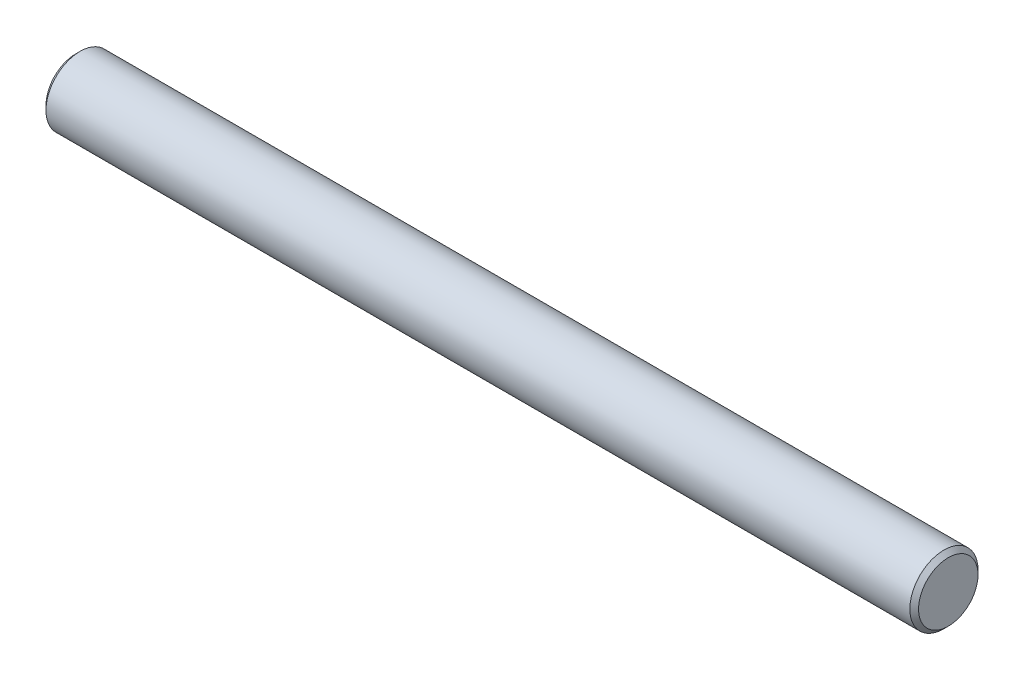
SolidWorks part; units mm, degrees
material "Plain Carbon Steel"
ref_plane "Спереди" through (0, 0, 0) normal (0, 0, 1) x (1, 0, 0)
ref_plane "Сверху" through (0, 0, 0) normal (0, 1, 0) x (1, 0, 0)
ref_plane "Справа" through (0, 0, 0) normal (1, 0, 0) x (0, 0, -1)
sketch "Sketch1" plane through (0, 0, 0) normal (0, 0, 1) x (1, 0, 0)
  line L0 (0, 0) -> (-128.9864, 0) construction
  line L1 (0, 0) -> (-320, 0)
  line L2 (-320, 0) -> (-320, 12.5)
  line L3 (-320, 12.5) -> (0, 12.5)
  line L4 (0, 12.5) -> (0, 0)
  dimension "D1" = 25
  dimension "D2" = 320
revolve "Revolve1" add sketch "Sketch1" angle 360 about L0
chamfer "Chamfer1" distance 1.6 angle 45 2 edges at (0, 0, -12.5) (-320, 0, -12.5)
hole_wizard "M10 Tapped Hole1" positions "Sketch3" profile "Sketch2" tap size "M10" standard "ISO"
sketch "Sketch3" plane through (-320, 0, 0) normal (-1, 0, 0) x (0, 0, 1)
  circle A0 centre (0, 0) radius 10.9 construction
  point P0 (0, 0)
sketch "Sketch2" plane through (-320, 0, 0) normal (0, 1, 0) x (0, 0, 1)
  line L0 (0, 0) -> (0, 27.0537)
  line L1 (0, 27.0537) -> (4.25, 24.5)
  line L2 (4.25, 24.5) -> (4.25, 20)
  line L3 (4.25, 20) -> (5, 20)
  line L4 (5, 20) -> (5, 0)
  line L5 (5, 0) -> (0, 0)
  line L10 (0, 27.0537) -> (-4.25, 24.5) construction
  line L11 (0, -6.35) -> (0, 107.95) construction
  dimension "Tap Drill Dia." = 8.5
  dimension "Tap Drill Depth" = 24.5
  dimension "Thread Major Dia." = 10
  dimension "Thread Depth" = 20
  dimension "Drill Angle" = 118
